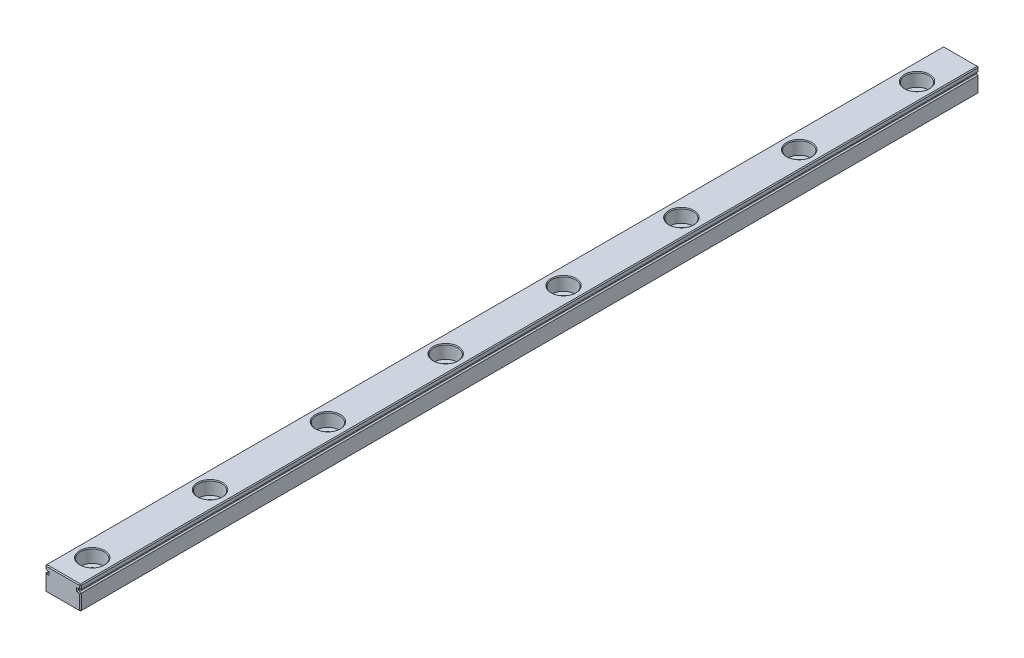
SolidWorks part; units mm, degrees
material "AISI 304"
ref_plane "Front Plane" through (0, 0, 0) normal (0, 0, 1) x (1, 0, 0)
ref_plane "Top Plane" through (0, 0, 0) normal (0, 1, 0) x (1, 0, 0)
ref_plane "Right Plane" through (0, 0, 0) normal (1, 0, 0) x (0, 0, -1)
sketch "Sketch1" plane through (0, 0, 0) normal (0, 0, 1) x (1, 0, 0)
  line L0 (0, 0) -> (0, 8) construction
  line L1 (0, 8) -> (12, 8)
  line L2 (0, 0) -> (12, 0)
  line L3 (0, 8) -> (0, 6.75)
  line L4 (0, 6.75) -> (0.5, 6.25) construction
  line L5 (0.5, 6.25) -> (1, 6.25)
  line L6 (0.5, 5.75) -> (0, 5.25) construction
  line L7 (0, 5.25) -> (0, 0)
  line L8 (1, 6.25) -> (1, 5.75)
  line L9 (1, 5.75) -> (0.5, 5.75)
  line L10 (0.5, 5.75) -> (0.75, 6) construction
  line L11 (0.75, 6) -> (0.5, 6.25) construction
  line L12 (0, 6.75) -> (0, 6.559)
  line L13 (0, 5.25) -> (0, 5.441)
  line L14 (6, 8) -> (6, 0) construction
  line L15 (11.25, 6) -> (11.5, 6.25) construction
  line L16 (11.5, 5.75) -> (11.25, 6) construction
  line L17 (11.5, 5.75) -> (12, 5.25) construction
  line L18 (12, 6.75) -> (11.5, 6.25) construction
  line L19 (12, 0) -> (12, 8) construction
  line L20 (12, 5.25) -> (12, 5.441)
  line L21 (12, 6.75) -> (12, 6.559)
  line L22 (11, 5.75) -> (11.5, 5.75)
  line L23 (11, 6.25) -> (11, 5.75)
  line L24 (12, 5.25) -> (12, 0)
  line L25 (11.5, 6.25) -> (11, 6.25)
  line L26 (12, 8) -> (12, 6.75)
  arc A0 (0, 5.441) -> (0.5, 5.75) centre (0, 6) ccw
  arc A1 (0.5, 6.25) -> (0, 6.559) centre (0, 6) ccw
  arc A2 (11.5, 6.25) -> (12, 6.559) centre (12, 6) cw
  arc A3 (12, 5.441) -> (11.5, 5.75) centre (12, 6) cw
  point P4 (1, 6)
  point P28 (11, 6)
  dimension "D1" = 8
  dimension "D2" = 6
  dimension "D3" = 0.5
  dimension "D4" = 45
  dimension "D5" = 2
  dimension "D6" = 1
extrude "Boss-Extrude1" add sketch "Sketch1" along normal blind 470
chamfer "Chamfer1" distance 0.3 angle 45 36 edges at (0, 0, 235) (12, 0, 235) (0, 8, 235) (12, 8, 235) (0.2939, 5.5245, 470) (0.75, 5.75, 470) (1, 6, 470) (0.75, 6.25, 470) (0.2939, 6.4755, 470) (0, 7.2795, 470) (6, 8, 470) (12, 7.2795, 470) (11.7061, 6.4755, 470) (11.25, 6.25, 470) (11, 6, 470) (11.25, 5.75, 470) (11.7061, 5.5245, 470) (12, 2.7205, 470) (6, 0, 470) (0, 2.7205, 470) (12, 2.7205, 0) (11.7061, 5.5245, 0) (11.25, 5.75, 0) (11, 6, 0) (11.25, 6.25, 0) (11.7061, 6.4755, 0) (12, 7.2795, 0) (6, 0, 0) (0, 2.7205, 0) (0.2939, 5.5245, 0) (0.75, 5.75, 0) (1, 6, 0) (0.75, 6.25, 0) (0.2939, 6.4755, 0) (0, 7.2795, 0) (6, 8, 0)
hole_wizard "CBORE for M5 Hex Head Bolt1" positions "3DSketch1" profile "Sketch3" counterbore size "M5" standard "ANSI Metric" end condition through all
sketch3d "3DSketch1"
  line L0 (6, 8, 0) -> (6, 8, 15) construction
  line L1 (11.7, 8, 0) -> (0.3, 8, 0) construction
  point P0 (6, 8, 15)
  dimension "D1" = 15
sketch "Sketch3" plane through (6, 8, 15) normal (1, 0, 0) x (0, 0, 1)
  line L0 (0, 0) -> (0, 8)
  line L1 (2.25, 7.75) -> (2.5, 8)
  line L2 (4, 4.5) -> (2.25, 4.5)
  line L3 (2.25, 4.5) -> (2.25, 7.75)
  line L5 (4, 4.5) -> (4, 0.25)
  line L6 (4, 0.25) -> (4.25, 0)
  line L7 (4.25, 0) -> (0, 0)
  line L8 (-4, 0.25) -> (-4.25, 0) construction
  line L11 (0, -6.35) -> (0, 107.95) construction
  line L12 (2.5, 8) -> (0, 8)
  line L13 (-2.25, 7.75) -> (-2.5, 8) construction
  dimension "Thru Hole Dia." = 4.5
  dimension "Thru Hole Depth" = 8
  dimension "C'Bore Dia." = 8
  dimension "C'Bore Depth" = 4.5
  dimension "Near C'Sink Dia." = 8.5
  dimension "Near C'Sink Angle" = 90
  dimension "Far C'Sink Dia." = 5
  dimension "Far C'Sink Angle" = 90
pattern_linear "LPattern1" count 12 spacing 40 along (0, 0, 1) of "CBORE for M5 Hex Head Bolt1"
sketch "Croquis1" plane through (0, 0, 470) normal (0, 0, 1) x (1, 0, 0)
  line L1 (-4.1596, 9.8274) -> (14.7316, 9.8274)
  line L2 (-4.1596, 9.8274) -> (-4.1596, -2.5781)
  line L3 (-4.1596, -2.5781) -> (14.7316, -2.5781)
  line L4 (14.7316, 9.8274) -> (14.7316, -2.5781)
extrude "Cortar-Extruir2" cut sketch "Croquis1" against normal blind 165
chamfer "Chaflán1" distance 0.3 angle 45 20 edges at (12, 2.8705, 305) (11.85, 0.15, 305) (6, 0, 305) (0.15, 0.15, 305) (0, 2.8705, 305) (0.2939, 5.5245, 305) (0.75, 5.75, 305) (1, 6, 305) (0.75, 6.25, 305) (0.2939, 6.4755, 305) (0, 7.1295, 305) (0.15, 7.85, 305) (6, 8, 305) (11.85, 7.85, 305) (12, 7.1295, 305) (11.7061, 6.4755, 305) (11.25, 6.25, 305) (11, 6, 305) (11.25, 5.75, 305) (11.7061, 5.5245, 305)
